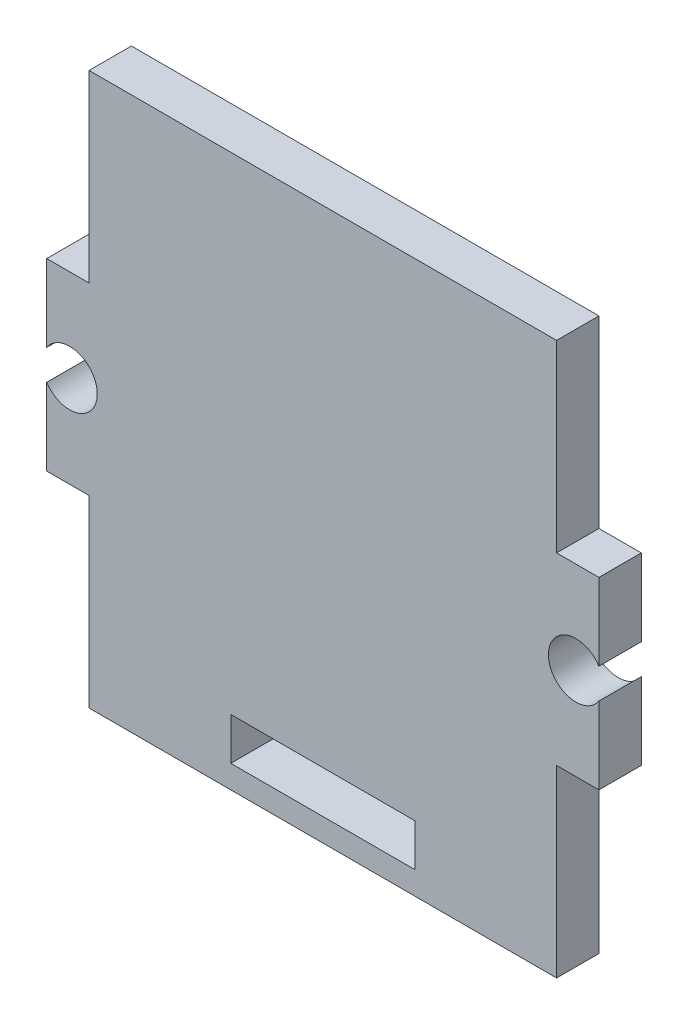
SolidWorks part; units mm, degrees
ref_plane "Front Plane" through (0, 0, 0) normal (0, 0, 1) x (1, 0, 0)
ref_plane "Top Plane" through (0, 0, 0) normal (0, 1, 0) x (1, 0, 0)
ref_plane "Right Plane" through (0, 0, 0) normal (1, 0, 0) x (0, 0, -1)
sketch "Sketch1" plane through (0, 0, 0) normal (0, 0, 1) x (1, 0, 0)
  line L0 (-2.921, 36.5125) -> (0, 36.5125) construction
  line L1 (0, -1.5875) -> (-38.1, -1.5875)
  line L2 (0, -1.5875) -> (0, 36.5125)
  line L3 (0, 36.5125) -> (-38.1, 36.5125)
  line L4 (-38.1, -1.5875) -> (-38.1, 36.5125)
  line L5 (-38.1, 2.921) -> (-38.1, 0) construction
extrude "Boss-Extrude1" add sketch "Sketch1" against normal blind 2.921 contours L4 L3 L2 L1
sketch "Sketch2" plane through (0, 0, 0) normal (0, 0, 1) x (1, 0, 0)
  line L4 (-25.4, 2.921) -> (-25.4, 0)
  line L5 (-25.4, 0) -> (-12.7, 0)
  line L6 (-12.7, 0) -> (-12.7, 2.921)
  line L7 (-12.7, 2.921) -> (-25.4, 2.921)
  line L8 (-25.4, 2.921) -> (-25.4, 0)
  line L9 (-25.4, 0) -> (-12.7, 0)
  line L10 (-12.7, 0) -> (-12.7, 2.921)
  line L11 (-12.7, 2.921) -> (-25.4, 2.921)
  dimension "D1" = 0
extrude "Cut-Extrude1" cut sketch "Sketch2" against normal through all
sketch "Sketch3" plane through (0, 0, 0) normal (0, 0, 1) x (1, 0, 0)
  line L0 (0, 11.1125) -> (-2.921, 11.1125) construction
  line L1 (-2.921, 11.1125) -> (-2.921, -1.5875) construction
  line L2 (-2.921, -1.5875) -> (0, -1.5875) construction
  line L3 (0, -1.5875) -> (0, 11.1125) construction
  line L4 (-2.921, 23.8125) -> (0, 23.8125) construction
  line L5 (0, 23.8125) -> (0, 36.5125) construction
  line L6 (0, 36.5125) -> (-2.921, 36.5125) construction
  line L7 (-2.921, 36.5125) -> (-2.921, 23.8125) construction
  line L8 (0, 11.1125) -> (-2.921, 11.1125)
  line L9 (-2.921, 11.1125) -> (-2.921, -1.5875)
  line L10 (-2.921, -1.5875) -> (0, -1.5875)
  line L11 (0, -1.5875) -> (0, 11.1125)
  line L12 (-2.921, 23.8125) -> (0, 23.8125)
  line L13 (0, 23.8125) -> (0, 36.5125)
  line L14 (0, 36.5125) -> (-2.921, 36.5125)
  line L15 (-2.921, 36.5125) -> (-2.921, 23.8125)
  line L17 (-19.05, 36.5125) -> (-19.05, -1.5875) construction
  line L18 (0, 36.5125) -> (-38.1, 36.5125) construction
  line L19 (0, -1.5875) -> (-38.1, -1.5875) construction
  line L20 (-35.179, 36.5125) -> (-35.179, 23.8125)
  line L21 (-38.1, 36.5125) -> (-35.179, 36.5125)
  line L22 (-38.1, 23.8125) -> (-38.1, 36.5125)
  line L23 (-35.179, 23.8125) -> (-38.1, 23.8125)
  line L24 (-38.1, -1.5875) -> (-38.1, 11.1125)
  line L25 (-35.179, -1.5875) -> (-38.1, -1.5875)
  line L26 (-35.179, 11.1125) -> (-35.179, -1.5875)
  line L27 (-38.1, 11.1125) -> (-35.179, 11.1125)
extrude "Cut-Extrude2" cut sketch "Sketch3" against normal through all
hole_wizard "#6 Clearance Hole2" positions "Sketch7" profile "Sketch6" hole size "#6" standard "ANSI Inch" end condition through all
sketch "Sketch7" plane through (0, 0, 0) normal (0, 0, 1) x (1, 0, 0)
  point P0 (-1.5875, 17.4625)
  point P2 (-36.5125, 17.4625)
sketch "Sketch6" plane through (-1.5875, 17.4625, 0) normal (1, 0, 0) x (0, -1, 0)
  line L0 (0, 0) -> (0, 2.921)
  line L1 (0, 2.921) -> (1.8986, 2.921)
  line L2 (1.8986, 2.921) -> (1.8986, 0)
  line L5 (1.8986, 0) -> (0, 0)
  line L11 (0, -6.35) -> (0, 107.95) construction
  dimension "Thru Hole Dia." = 3.7973
  dimension "Thru Hole Depth" = 2.921
equation "\"D1@Boss-Extrude1\"=\"thick@boxassy1.sldasm\""
